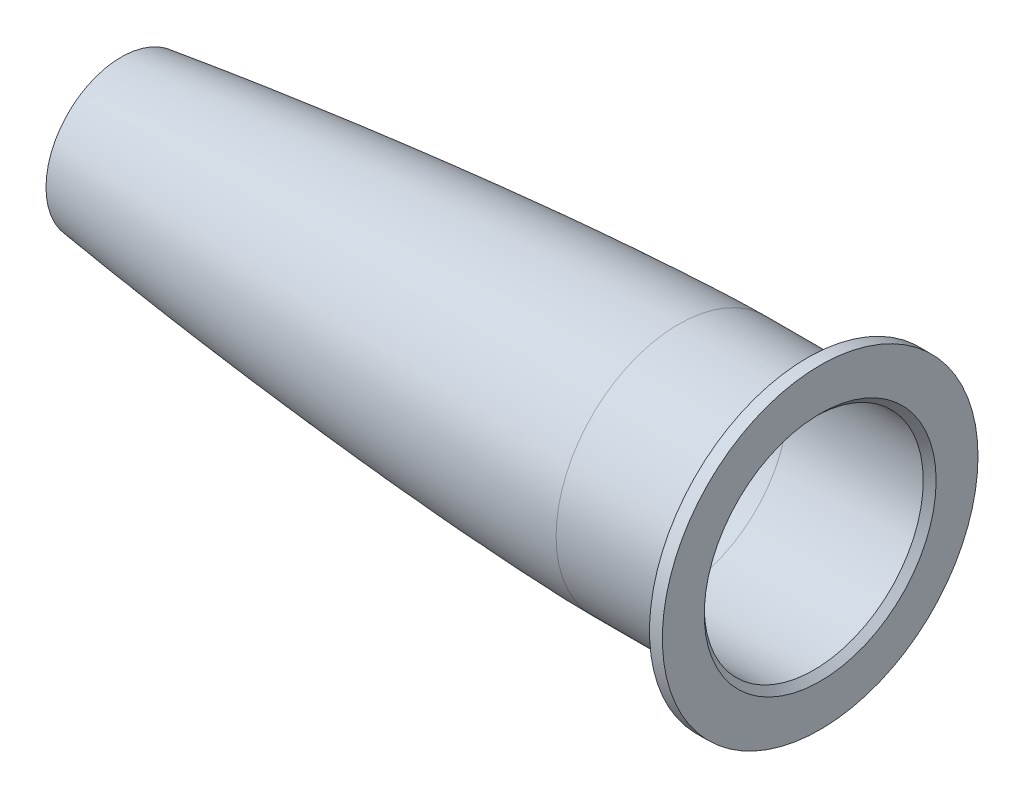
SolidWorks part; units mm, degrees
ref_plane "Front Plane" through (0, 0, 0) normal (0, 0, 1) x (1, 0, 0)
ref_plane "Top Plane" through (0, 0, 0) normal (0, 1, 0) x (1, 0, 0)
ref_plane "Right Plane" through (0, 0, 0) normal (1, 0, 0) x (0, 0, -1)
curve "Curve1"
  spline degree 3 poles (0, 0, 0) (0.3239, 0.2563, 0) (0.9404, 0.7441, 0) (1.9928, 1.2129, 0) (2.9928, 1.6503, 0) (3.9962, 2.0429, 0) (4.997, 2.4136, 0) (5.9977, 2.765, 0) (6.9982, 3.102, 0) (7.9985, 3.4266, 0) (8.9987, 3.7409, 0) (9.9989, 4.0463, 0) (10.999, 4.3437, 0) (11.9992, 4.6341, 0) (12.9993, 4.9182, 0) (13.9993, 5.1965, 0) (14.9994, 5.4695, 0) (15.9994, 5.7378, 0) (16.9995, 6.0015, 0) (17.9995, 6.261, 0) (18.9996, 6.5167, 0) (19.9996, 6.7687, 0) (20.9996, 7.0173, 0) (21.9996, 7.2626, 0) (22.9997, 7.5048, 0) (23.9997, 7.7441, 0) (24.9997, 7.9806, 0) (25.9997, 8.2145, 0) (26.9997, 8.4458, 0) (27.9997, 8.6747, 0) (28.9998, 8.9012, 0) (29.9998, 9.1256, 0) (30.9998, 9.3477, 0) (31.9998, 9.5678, 0) (32.9998, 9.7859, 0) (33.9998, 10.0021, 0) (34.9998, 10.2164, 0) (35.9998, 10.4289, 0) (36.9998, 10.6396, 0) (37.9998, 10.8486, 0) (38.9998, 11.056, 0) (39.9998, 11.2617, 0) (40.9999, 11.4659, 0) (41.9999, 11.6686, 0) (42.9999, 11.8698, 0) (43.9999, 12.0696, 0) (44.9999, 12.2679, 0) (45.9999, 12.4649, 0) (46.9999, 12.6605, 0) (47.9999, 12.8548, 0) (48.9999, 13.0478, 0) (49.9999, 13.2396, 0) (50.9999, 13.4301, 0) (51.9999, 13.6194, 0) (52.9999, 13.8076, 0) (53.9999, 13.9946, 0) (54.9999, 14.1804, 0) (55.9999, 14.3652, 0) (56.9999, 14.5488, 0) (57.9999, 14.7314, 0) (58.9999, 14.9129, 0) (59.9999, 15.0934, 0) (60.9999, 15.2728, 0) (61.9999, 15.4513, 0) (62.9999, 15.6288, 0) (63.9999, 15.8052, 0) (64.9999, 15.9808, 0) (65.9999, 16.1554, 0) (66.9999, 16.329, 0) (67.9999, 16.5018, 0) (68.9999, 16.6736, 0) (69.9999, 16.8445, 0) (70.9999, 17.0146, 0) (71.9999, 17.1838, 0) (72.9999, 17.3522, 0) (73.9999, 17.5197, 0) (74.9999, 17.6863, 0) (75.9999, 17.8522, 0) (76.9999, 18.0172, 0) (77.9999, 18.1814, 0) (78.9999, 18.3449, 0) (79.9999, 18.5075, 0) (80.9999, 18.6694, 0) (81.9999, 18.8305, 0) (82.9999, 18.9908, 0) (83.9999, 19.1504, 0) (84.9999, 19.3092, 0) (85.9999, 19.4673, 0) (86.9999, 19.6247, 0) (87.9999, 19.7814, 0) (88.9999, 19.9373, 0) (89.9999, 20.0925, 0) (90.9999, 20.2471, 0) (91.9999, 20.4009, 0) (92.9999, 20.554, 0) (93.9999, 20.7065, 0) (95, 20.8583, 0) (96, 21.0094, 0) (97, 21.1598, 0) (98, 21.3096, 0) (99, 21.4587, 0) (100, 21.6072, 0) (101, 21.755, 0) (102, 21.9022, 0) (103, 22.0488, 0) (104, 22.1947, 0) (105, 22.34, 0) (106, 22.4846, 0) (107, 22.6287, 0) (108, 22.7721, 0) (109, 22.915, 0) (110, 23.0572, 0) (111, 23.1988, 0) (112, 23.3398, 0) (113, 23.4803, 0) (114, 23.6201, 0) (115, 23.7594, 0) (116, 23.898, 0) (117, 24.0361, 0) (118, 24.1736, 0) (119, 24.3106, 0) (120, 24.4469, 0) (121, 24.5827, 0) (122, 24.718, 0) (123, 24.8526, 0) (124, 24.9867, 0) (125, 25.1203, 0) (126, 25.2533, 0) (127, 25.3857, 0) (128, 25.5176, 0) (129, 25.649, 0) (130, 25.7798, 0) (131, 25.91, 0) (132, 26.0397, 0) (133, 26.1689, 0) (134, 26.2975, 0) (135, 26.4257, 0) (136, 26.5532, 0) (137, 26.6803, 0) (138, 26.8068, 0) (139, 26.9328, 0) (140, 27.0582, 0) (141, 27.1832, 0) (142, 27.3076, 0) (143, 27.4315, 0) (144, 27.5549, 0) (145, 27.6777, 0) (146, 27.8001, 0) (147, 27.9219, 0) (148, 28.0432, 0) (149, 28.1641, 0) (150, 28.2844, 0) (151, 28.4041, 0) (152, 28.5234, 0) (153, 28.6422, 0) (154, 28.7605, 0) (155, 28.8782, 0) (156, 28.9955, 0) (157, 29.1122, 0) (158, 29.2285, 0) (159, 29.3442, 0) (160, 29.4595, 0) (161, 29.5742, 0) (162, 29.6885, 0) (163, 29.8022, 0) (164, 29.9155, 0) (165, 30.0282, 0) (166, 30.1405, 0) (167, 30.2522, 0) (168, 30.3635, 0) (169, 30.4743, 0) (170, 30.5845, 0) (171, 30.6943, 0) (172, 30.8036, 0) (173, 30.9124, 0) (174, 31.0207, 0) (175, 31.1285, 0) (176, 31.2358, 0) (177, 31.3426, 0) (178, 31.4489, 0) (179, 31.5547, 0) (180, 31.66, 0) (181, 31.7649, 0) (182, 31.8692, 0) (183, 31.973, 0) (184, 32.0764, 0) (185, 32.1792, 0) (186, 32.2816, 0) (187, 32.3834, 0) (188, 32.4848, 0) (189, 32.5856, 0) (190, 32.686, 0) (191, 32.7859, 0) (192, 32.8852, 0) (193, 32.9841, 0) (194, 33.0825, 0) (195, 33.1803, 0) (196, 33.2777, 0) (197, 33.3746, 0) (198, 33.4709, 0) (199, 33.5668, 0) (200, 33.6621, 0) (201, 33.757, 0) (202, 33.8513, 0) (203, 33.9451, 0) (204, 34.0385, 0) (205, 34.1313, 0) (206, 34.2236, 0) (207, 34.3153, 0) (208, 34.4066, 0) (209, 34.4973, 0) (210, 34.5876, 0) (211, 34.6773, 0) (212, 34.7665, 0) (213, 34.8551, 0) (214, 34.9433, 0) (215, 35.0309, 0) (216, 35.118, 0) (217, 35.2045, 0) (218, 35.2906, 0) (219, 35.3761, 0) (220, 35.461, 0) (221, 35.5454, 0) (222, 35.6293, 0) (223, 35.7126, 0) (224, 35.7954, 0) (225, 35.8776, 0) (226, 35.9593, 0) (227, 36.0404, 0) (228, 36.121, 0) (229, 36.201, 0) (230, 36.2805, 0) (231, 36.3594, 0) (232, 36.4377, 0) (233, 36.5154, 0) (234, 36.5926, 0) (235, 36.6692, 0) (236, 36.7452, 0) (237, 36.8206, 0) (238, 36.8954, 0) (239, 36.9696, 0) (240, 37.0432, 0) (241, 37.1163, 0) (242, 37.1887, 0) (243, 37.2605, 0) (244, 37.3317, 0) (245, 37.4022, 0) (246, 37.4722, 0) (247, 37.5415, 0) (248, 37.6102, 0) (249, 37.6782, 0) (250, 37.7455, 0) (251, 37.8123, 0) (252, 37.8783, 0) (253, 37.9437, 0) (254, 38.0084, 0) (255, 38.0725, 0) (256, 38.1358, 0) (257, 38.1985, 0) (258, 38.2604, 0) (259, 38.3216, 0) (260, 38.3821, 0) (261, 38.4419, 0) (262, 38.5009, 0) (263, 38.5592, 0) (264, 38.6168, 0) (265, 38.6735, 0) (266, 38.7295, 0) (267, 38.7847, 0) (268, 38.8391, 0) (269, 38.8926, 0) (270, 38.9454, 0) (271, 38.9972, 0) (272, 39.0483, 0) (273, 39.0984, 0) (274, 39.1477, 0) (275, 39.196, 0) (276, 39.2434, 0) (277, 39.2899, 0) (278, 39.3354, 0) (279, 39.3799, 0) (280, 39.4234, 0) (281, 39.4658, 0) (282, 39.5072, 0) (283, 39.5475, 0) (284, 39.5866, 0) (285, 39.6246, 0) (286, 39.6613, 0) (287, 39.6968, 0) (288, 39.731, 0) (289, 39.7638, 0) (290, 39.7952, 0) (291, 39.8251, 0) (292, 39.8533, 0) (293, 39.88, 0) (294, 39.9048, 0) (295, 39.9276, 0) (296, 39.9483, 0) (297, 39.9666, 0) (298, 39.982, 0) (299, 39.9947, 0) (299.6667, 39.9982, 0) (300, 40, 0) knots 0 0 0 0 0.004064 0.007736 0.011323 0.014865 0.018378 0.021871 0.025347 0.028811 0.032264 0.035709 0.039146 0.042576 0.046001 0.04942 0.052835 0.056246 0.059653 0.063056 0.066457 0.069854 0.073248 0.07664 0.08003 0.083417 0.086802 0.090186 0.093567 0.096946 0.100324 0.1037 0.107075 0.110448 0.11382 0.11719 0.120559 0.123927 0.127294 0.130659 0.134023 0.137387 0.140749 0.14411 0.14747 0.15083 0.154188 0.157546 0.160902 0.164258 0.167613 0.170968 0.174321 0.177674 0.181026 0.184378 0.187728 0.191078 0.194428 0.197776 0.201124 0.204472 0.207819 0.211165 0.214511 0.217856 0.221201 0.224545 0.227888 0.231231 0.234574 0.237916 0.241258 0.244599 0.247939 0.251279 0.254619 0.257958 0.261297 0.264636 0.267974 0.271311 0.274648 0.277985 0.281321 0.284657 0.287993 0.291328 0.294663 0.297997 0.301331 0.304665 0.307999 0.311332 0.314664 0.317997 0.321329 0.32466 0.327992 0.331323 0.334653 0.337984 0.341314 0.344643 0.347973 0.351302 0.354631 0.35796 0.361288 0.364616 0.367943 0.371271 0.374598 0.377925 0.381251 0.384578 0.387904 0.39123 0.394555 0.39788 0.401205 0.40453 0.407855 0.411179 0.414503 0.417827 0.42115 0.424474 0.427797 0.431119 0.434442 0.437764 0.441086 0.444408 0.44773 0.451051 0.454372 0.457693 0.461014 0.464335 0.467655 0.470975 0.474295 0.477615 0.480934 0.484253 0.487572 0.490891 0.49421 0.497528 0.500846 0.504165 0.507482 0.5108 0.514117 0.517435 0.520752 0.524068 0.527385 0.530702 0.534018 0.537334 0.54065 0.543965 0.547281 0.550596 0.553911 0.557226 0.560541 0.563856 0.56717 0.570484 0.573799 0.577112 0.580426 0.58374 0.587053 0.590366 0.593679 0.596992 0.600305 0.603617 0.606929 0.610242 0.613554 0.616865 0.620177 0.623489 0.6268 0.630111 0.633422 0.636733 0.640043 0.643354 0.646664 0.649974 0.653284 0.656594 0.659904 0.663213 0.666523 0.669832 0.673141 0.67645 0.679759 0.683067 0.686376 0.689684 0.692992 0.6963 0.699608 0.702916 0.706223 0.70953 0.712838 0.716145 0.719452 0.722758 0.726065 0.729371 0.732678 0.735984 0.73929 0.742596 0.745901 0.749207 0.752512 0.755817 0.759122 0.762427 0.765732 0.769037 0.772341 0.775646 0.77895 0.782254 0.785558 0.788862 0.792165 0.795469 0.798772 0.802075 0.805378 0.808681 0.811984 0.815287 0.818589 0.821891 0.825193 0.828496 0.831797 0.835099 0.838401 0.841702 0.845003 0.848305 0.851606 0.854907 0.858207 0.861508 0.864808 0.868109 0.871409 0.874709 0.878009 0.881308 0.884608 0.887907 0.891207 0.894506 0.897805 0.901104 0.904402 0.907701 0.910999 0.914297 0.917596 0.920894 0.924191 0.927489 0.930787 0.934084 0.937381 0.940678 0.943975 0.947272 0.950569 0.953865 0.957161 0.960458 0.963754 0.96705 0.970345 0.973641 0.976936 0.980232 0.983527 0.986822 0.990117 0.993411 0.996706 1 1 1 1
sketch "Sketch2" plane through (0, 0, 0) normal (0, 0, 1) x (1, 0, 0)
  line L0 (0, 0) -> (125, 0) construction
  line L2 (300, 40) -> (300.0106, 38) construction
  line L3 (0, 0) -> (4.2671, 0)
  line L4 (300, 40) -> (340, 40)
  line L5 (340, 40) -> (340, 38)
  line L6 (340, 38) -> (300.0106, 38)
  line L7 (125, 25.1202) -> (125, 23.1025)
  line L8 (125, 0) -> (127, 0) construction
  line L9 (127, 0) -> (127, 23.3682)
  line L10 (340, 38) -> (340, 34)
  line L11 (340, 34) -> (300.0106, 34)
  line L12 (127, 0) -> (131, 0)
  line L13 (131, 0) -> (131, 20)
  line L14 (127, 0) -> (131, 0)
  line L15 (125, 0) -> (127, 0) construction
  line L16 (127, 0) -> (1129.646, 0) construction
  line L17 (125, 23.1025) -> (125, 0) construction
  arc A0 (300.0106, 34) -> (131, 20) centre (348.2024, -1574.9403) ccw
  spline S0 degree 3 poles (-1605.8079, 2533.2499) (16.7759, -86.5021) (-13.4623, -5.6713) (1.9928, 1.2129) (2.9928, 1.6503) (3.9962, 2.0429) (4.997, 2.4136) (5.9977, 2.765) (6.9982, 3.102) (7.9985, 3.4266) (8.9987, 3.7409) (9.9989, 4.0463) (10.999, 4.3437) (11.9992, 4.6341) (12.9993, 4.9182) (13.9993, 5.1965) (14.9994, 5.4695) (15.9994, 5.7378) (17.3322, 6.0892) (18.9983, 6.5182) (20.9985, 7.0186) (22.9987, 7.506) (24.9988, 7.9817) (26.9989, 8.4468) (28.999, 8.9022) (31.332, 9.4229) (33.9983, 10.0043) (36.9985, 10.6416) (39.9986, 11.2636) (42.9987, 11.8715) (46.3318, 12.5325) (49.9982, 13.2423) (53.9984, 13.9971) (57.9985, 14.7338) (62.3316, 15.5134) (66.9981, 16.3324) (71.9982, 17.187) (77.3314, 18.0757) (82.9979, 18.9949) (88.9981, 19.9411) (95.3312, 20.913) (101.9978, 21.907) (108.9979, 22.9195) (116.3311, 23.9492) (123.9977, 24.9923) (131.9978, 26.0451) (140.331, 27.1059) (148.9975, 28.1706) (157.9977, 29.2349) (166.9978, 30.2586) (175.9979, 31.2421) (184.998, 32.1856) (193.998, 33.089) (202.665, 33.9198) (210.9985, 34.6826) (218.6654, 35.3525) (225.9989, 35.9637) (232.9989, 36.5199) (239.6657, 37.0229) (245.9992, 37.4758) (251.666, 37.8596) (256.9995, 38.2012) (261.6662, 38.4837) (265.9996, 38.7315) (269.9996, 38.9474) (273.6664, 39.1331) (276.9998, 39.2912) (279.9998, 39.4248) (282.6665, 39.5352) (284.9999, 39.6252) (286.9999, 39.6975) (288.9999, 39.7645) (290.6666, 39.8156) (292.3333, 39.8628) (293.6666, 39.8971) (295, 39.9276) (296, 39.9483) (297, 39.9666) (298, 39.982) (343.7491, 40.5639) (389.362, 18.16) (408.5654, 3036.1615) knots -0.154953 -0.154953 -0.154953 -0.154953 0.004064 0.007736 0.011323 0.014865 0.018378 0.021871 0.025347 0.028811 0.032264 0.035709 0.039146 0.042576 0.046001 0.04942 0.052835 0.056246 0.059653 0.066457 0.073248 0.08003 0.086802 0.093567 0.100324 0.107075 0.11719 0.127294 0.137387 0.14747 0.157546 0.170968 0.184378 0.197776 0.211165 0.227888 0.244599 0.261297 0.281321 0.301331 0.321329 0.344643 0.367943 0.39123 0.417827 0.444408 0.470975 0.500846 0.530702 0.560541 0.590366 0.620177 0.649974 0.679759 0.706223 0.732678 0.755817 0.77895 0.802075 0.821891 0.841702 0.858207 0.874709 0.887907 0.901104 0.914297 0.924191 0.934084 0.943975 0.950569 0.957161 0.963754 0.970345 0.973641 0.980232 0.983527 0.986822 0.990117 0.993411 0.996706 1.44228 1.44228 1.44228 1.44228 only from (0, 0) to (300, 40) construction
  spline S1 degree 3 poles (125, 25.1202) (128.3322, 25.5643) (134.6636, 26.3906) (143.9975, 27.5615) (152.9976, 28.6487) (161.9977, 29.6949) (170.9978, 30.7007) (179.9979, 31.6664) (188.998, 32.5921) (197.6649, 33.4447) (205.9985, 34.2288) (213.9985, 34.9487) (221.6654, 35.6063) (228.9989, 36.2054) (235.6657, 36.7239) (241.9992, 37.1922) (247.9992, 37.6138) (253.666, 37.9902) (258.9995, 38.3245) (263.6662, 38.6001) (267.9996, 38.8411) (271.9996, 39.0504) (275.6664, 39.2295) (278.9998, 39.3813) (281.9998, 39.5087) (284.6665, 39.6131) (286.9999, 39.6975) (288.9999, 39.7645) (290.6666, 39.8156) (292.3333, 39.8628) (293.6666, 39.8971) (295, 39.9276) (296, 39.9483) (297, 39.9666) (298, 39.982) (299, 39.9947) (299.6667, 39.9982) (300, 40) knots 0.42115 0.42115 0.42115 0.42115 0.454372 0.484253 0.514117 0.543965 0.573799 0.603617 0.633422 0.663213 0.689684 0.716145 0.742596 0.765732 0.788862 0.808681 0.828496 0.848305 0.864808 0.881308 0.894506 0.907701 0.920894 0.930787 0.940678 0.950569 0.957161 0.963754 0.970345 0.973641 0.980232 0.983527 0.986822 0.990117 0.993411 0.996706 1 1 1 1 construction
  spline S2 degree 1 poles (125.2642, 23.1377) (300.0106, 38) knots 0 0 1 1 construction
  spline S3 degree 3 poles (125.2642, 23.1377) (125.6981, 23.1956) (126.4214, 23.2917) (140.9222, 25.2103) (169.5342, 28.6684) (205.201, 32.2375) (234.3548, 34.6602) (256.2397, 36.2005) (274.4836, 37.2162) (289.0918, 37.7888) (296.3679, 37.9808) (300.0106, 38) knots 0.42115 0.42115 0.42115 0.42115 0.425481 0.428368 0.565863 0.710575 0.782931 0.855288 0.927644 0.963822 1 1 1 1 only from (127, 23.3682) to (300.0106, 38)
  spline S4 degree 3 poles (0, 0) (0.3239, 0.2563) (0.9404, 0.7441) (1.9928, 1.2129) (2.9928, 1.6503) (3.9962, 2.0429) (4.997, 2.4136) (5.9977, 2.765) (6.9982, 3.102) (7.9985, 3.4266) (8.9987, 3.7409) (9.9989, 4.0463) (10.999, 4.3437) (11.9992, 4.6341) (12.9993, 4.9182) (13.9993, 5.1965) (14.9994, 5.4695) (15.9994, 5.7378) (17.3322, 6.0892) (18.9983, 6.5182) (20.9985, 7.0186) (22.9987, 7.506) (24.9988, 7.9817) (26.9989, 8.4468) (28.999, 8.9022) (31.332, 9.4229) (33.9983, 10.0043) (36.9985, 10.6416) (39.9986, 11.2636) (42.9987, 11.8715) (46.3318, 12.5325) (49.9982, 13.2423) (53.9984, 13.9971) (57.9985, 14.7338) (62.3316, 15.5134) (66.9981, 16.3324) (71.9982, 17.187) (77.3314, 18.0757) (82.9979, 18.9949) (88.9981, 19.9411) (95.3312, 20.913) (101.9978, 21.907) (108.9979, 22.9195) (116.3311, 23.9492) (121.6658, 24.675) (124.6667, 25.0758) (125, 25.1202) knots 0 0 0 0 0.004064 0.007736 0.011323 0.014865 0.018378 0.021871 0.025347 0.028811 0.032264 0.035709 0.039146 0.042576 0.046001 0.04942 0.052835 0.056246 0.059653 0.066457 0.073248 0.08003 0.086802 0.093567 0.100324 0.107075 0.11719 0.127294 0.137387 0.14747 0.157546 0.170968 0.184378 0.197776 0.211165 0.227888 0.244599 0.261297 0.281321 0.301331 0.321329 0.344643 0.367943 0.39123 0.417827 0.42115 0.42115 0.42115 0.42115 construction
  spline S5 degree 3 poles (4.2671, 0) (4.3107, 0.0171) (4.5258, 0.1012) (5.4558, 0.4556) (7.0834, 1.031) (10.037, 1.984) (13.7867, 3.0797) (18.3317, 4.2942) (22.9057, 5.4346) (29.0314, 6.8774) (36.7255, 8.5622) (45.9958, 10.445) (55.293, 12.2166) (64.6107, 13.8956) (77.0563, 16.0277) (92.6469, 18.5165) (108.7755, 20.885) (119.566, 22.3741) (124.1012, 22.9826) (125, 23.1025) knots 0.013225 0.013225 0.013225 0.013225 0.013714 0.015625 0.023438 0.03125 0.046875 0.0625 0.078125 0.09375 0.125 0.15625 0.1875 0.21875 0.25 0.3125 0.375 0.4113 0.420271 0.420271 0.420271 0.420271 construction
  spline S6 degree 3 poles (125, 23.1025) (125.6666, 23.1914) (126.3333, 23.28) (127, 23.3682) knots 0.420271 0.420271 0.420271 0.420271 0.426925 0.426925 0.426925 0.426925 construction
  point P21 (131.5247, 19.4597)
  dimension "D7" = 1609.6619
  dimension "D2" = 40
  dimension "D3" = 2
  dimension "D4" = 175
  dimension "D5" = 4
  dimension "D6" = 4
  dimension "D8" = 20
  dimension "D1" = 2
revolve "Revolve1" add sketch "Sketch2" angle 360 about L0
sketch "Sketch3" plane through (125, 0, 0) normal (-1, 0, 0) x (0, 0, 1)
  circle A2 centre (0, 0) radius 3.1
  dimension "D1" = 6.2
extrude "Cut-Extrude1" cut sketch "Sketch3" against normal through all
sketch "Sketch4" plane through (340, 0, 0) normal (1, 0, 0) x (0, 0, -1)
  circle A0 centre (0, 0) radius 34
  circle A1 centre (0, 0) radius 49
  circle A2 centre (0, 0) radius 34 construction
  dimension "D1" = 15
extrude "Boss-Extrude1" add sketch "Sketch4" along normal blind 4
chamfer "Chamfer1" distance 2 angle 45 1 edges at (344, 0, -34)
sketch "Sketch5" plane through (127, 0, 0) normal (-1, 0, 0) x (0, 0, 1)
  line L0 (0, 15) -> (0, -15) construction
  line L1 (15, 0) -> (-15, 0) construction
  circle A0 centre (0, 15) radius 1.5
  circle A1 centre (15, 0) radius 1.5
  circle A2 centre (-15, 0) radius 1.5
  circle A3 centre (0, -15) radius 1.5
  dimension "D1" = 3
  dimension "D2" = 30
extrude "Boss-Extrude2" add sketch "Sketch5" along normal blind 2
